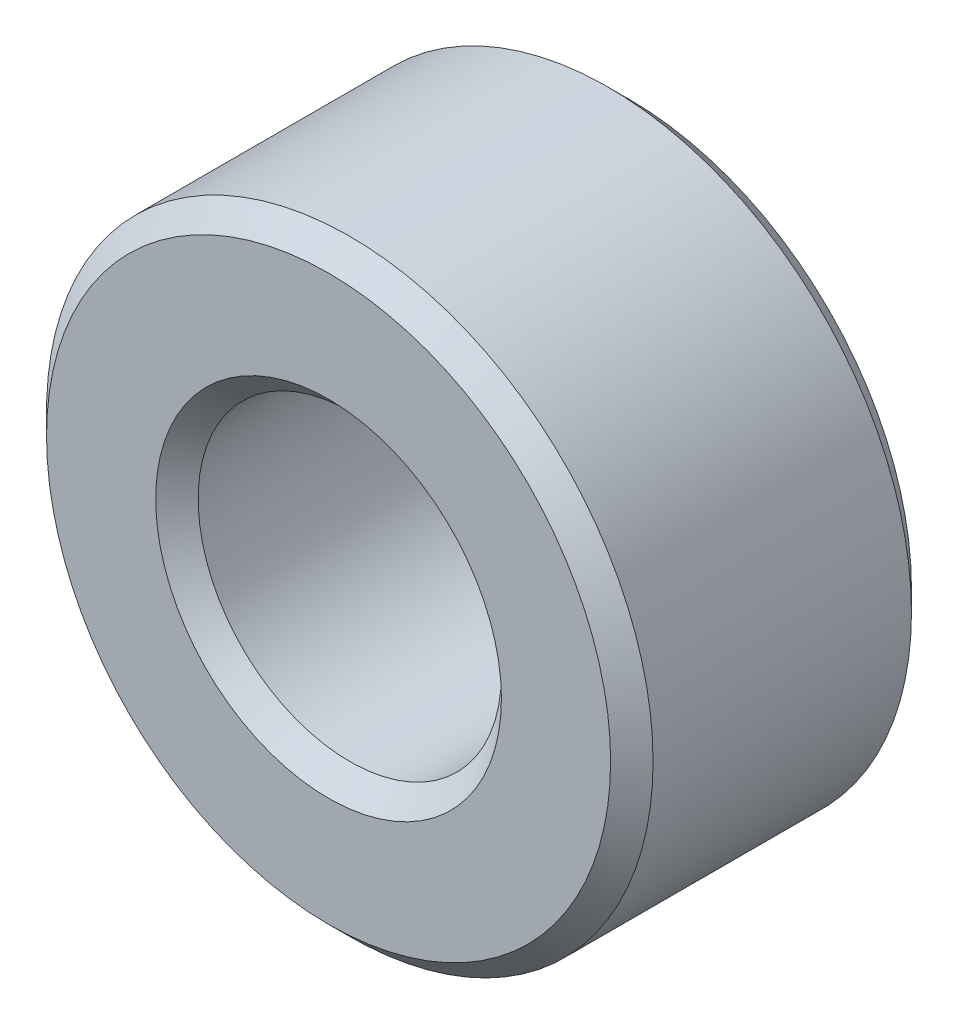
SolidWorks part; units mm, degrees
ref_plane "Front Plane" through (0, 0, 0) normal (0, 0, 1) x (1, 0, 0)
ref_plane "Top Plane" through (0, 0, 0) normal (0, 1, 0) x (1, 0, 0)
ref_plane "Right Plane" through (0, 0, 0) normal (1, 0, 0) x (0, 0, -1)
sketch "Sketch1" plane through (0, 0, 0) normal (0, 0, 1) x (1, 0, 0)
  line L0 (1.6002, 0) -> (3.2004, 0) construction
  circle A0 centre (0, 0) radius 1.6002 construction
  circle A1 centre (0, 0) radius 3.2004 construction
  circle A2 centre (0, 0) radius 3.175 construction
  circle A3 centre (0, 0) radius 1.5875 construction
  dimension "For Shaft Diameter" = 3.175
  dimension "For Housing ID" = 6.35
  dimension "OD" = 6.4008
  dimension "ID" = 3.2004
  dimension "D3" = 1.6002
sketch "Sketch13" plane through (0, 0, 0) normal (1, 0, 0) x (0, 0, -1)
  line L0 (1.5875, 0) -> (-1.5875, 0) construction
  line L1 (1.5875, 3.2004) -> (-1.5875, 3.2004) construction
  line L2 (0, 3.2004) -> (0, -3.2004) construction
  line L3 (0, 3.2004) -> (0, -3.2004) construction
  point P4 (0, 0)
  point P8 (0, 3.2004)
  dimension "Length" = 3.175
sketch "Sketch14" plane through (0, 0, 0) normal (0, 0, 1) x (1, 0, 0)
  circle A0 centre (0, 0) radius 1.6002 construction
  circle A1 centre (0, 0) radius 3.2004 construction
  circle A2 centre (0, 0) radius 1.6002
  circle A3 centre (0, 0) radius 3.2004
extrude "Boss-Extrude1" add sketch "Sketch14" against normal up to vertex (1.5875 mm away) and the other way up to vertex (1.5875 mm away) up to point (0, 3.2004, -1.5875) other way up to point (0, 3.2004, 1.5875)
chamfer "Chamfer1" distance 0.224 angle 45 4 edges at (3.2004, 0, -1.5875) (1.6002, 0, -1.5875) (1.6002, 0, 1.5875) (3.2004, 0, 1.5875)
equation "\"D1@Chamfer1\"=(\"OD@Sketch1\"-\"ID@Sketch1\")*.07"
